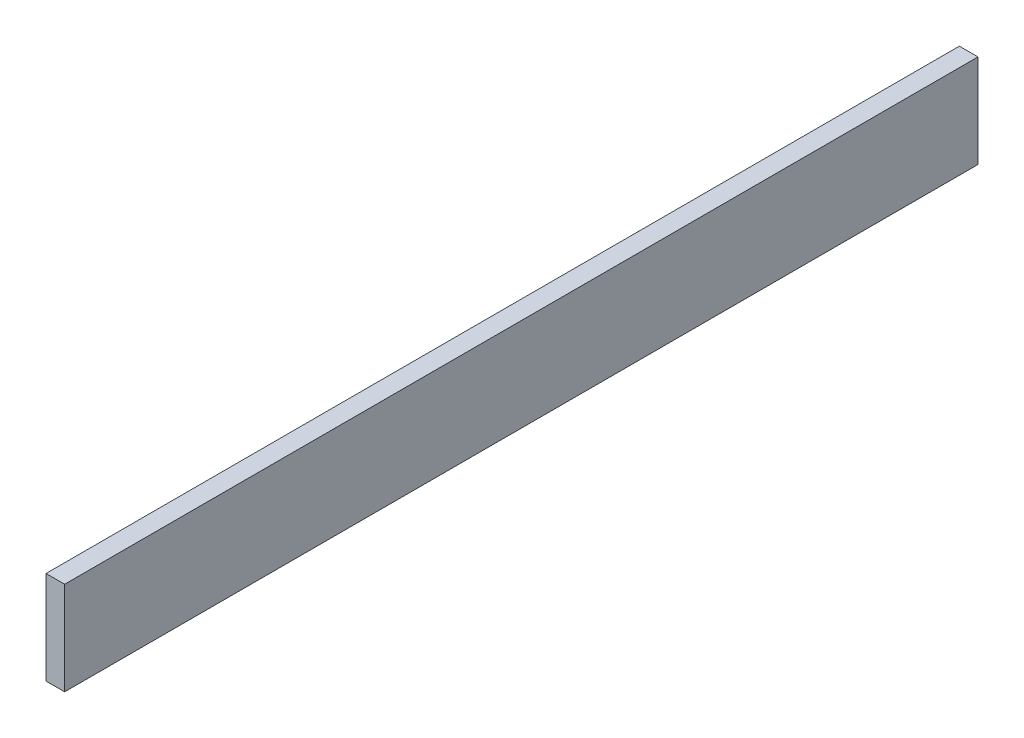
SolidWorks part; units mm, degrees
ref_plane "Front Plane" through (0, 0, 0) normal (0, 0, 1) x (1, 0, 0)
ref_plane "Top Plane" through (0, 0, 0) normal (0, 1, 0) x (1, 0, 0)
ref_plane "Right Plane" through (0, 0, 0) normal (1, 0, 0) x (0, 0, -1)
sketch "Sketch1" plane through (0, 0, 0) normal (1, 0, 0) x (0, 0, -1)
  line L1 (0, 0) -> (622.3, 0)
  line L2 (0, 0) -> (0, 63.5)
  line L3 (0, 63.5) -> (622.3, 63.5)
  line L4 (622.3, 0) -> (622.3, 63.5)
  dimension "D1" = 622.3
  dimension "D2" = 63.5
extrude "Boss-Extrude1" add sketch "Sketch1" along normal blind 12.7
